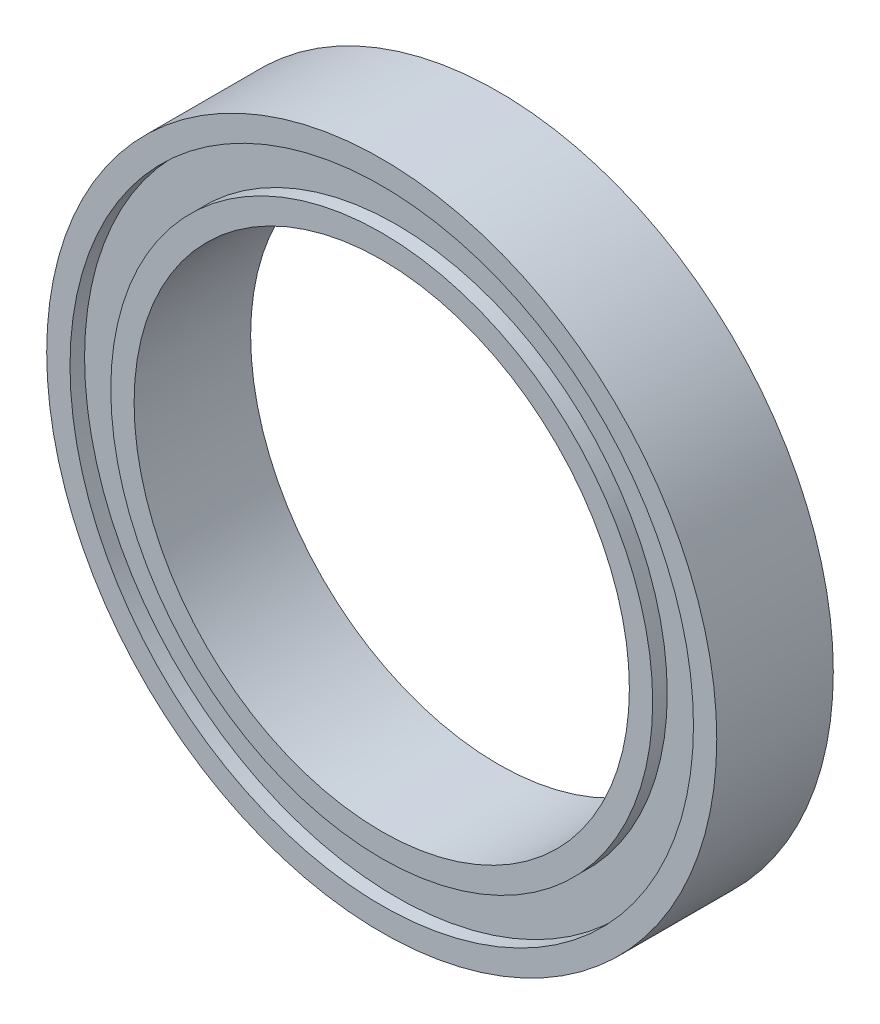
SolidWorks part; units mm, degrees
material "1023 碳钢板 (SS)"
ref_plane "前视基准面" through (0, 0, 0) normal (0, 0, 1) x (1, 0, 0)
ref_plane "上视基准面" through (0, 0, 0) normal (0, 1, 0) x (1, 0, 0)
ref_plane "右视基准面" through (0, 0, 0) normal (1, 0, 0) x (0, 0, -1)
other "Configuration Table"
sketch "草图1" plane through (0, 0, 0) normal (0, 0, 1) x (1, 0, 0)
  circle A0 centre (0, 0) radius 8.5
  circle A1 centre (0, 0) radius 11.5
  dimension "D1" = 17
  dimension "D2" = 23
extrude "凸台-拉伸1" add sketch "草图1" along normal blind 4
sketch "草图2" plane through (0, 0, 4) normal (0, 0, 1) x (1, 0, 0)
  circle A0 centre (0, 0) radius 10.7
  circle A1 centre (0, 0) radius 9.3
  circle A2 centre (0, 0) radius 11.5 construction
  circle A3 centre (0, 0) radius 8.5 construction
  dimension "D1" = 0.8
  dimension "D2" = 0.8
extrude "切除-拉伸1" cut sketch "草图2" against normal blind 0.5
sketch "草图3" plane through (0, 0, 0) normal (0, 0, -1) x (-1, 0, 0)
  circle A0 centre (0, 0) radius 10.7
  circle A1 centre (0, 0) radius 9.3
  circle A2 centre (0, 0) radius 8.5 construction
  circle A3 centre (0, 0) radius 11.5 construction
  dimension "D1" = 0.8
  dimension "D2" = 0.8
extrude "切除-拉伸2" cut sketch "草图3" against normal blind 0.5
